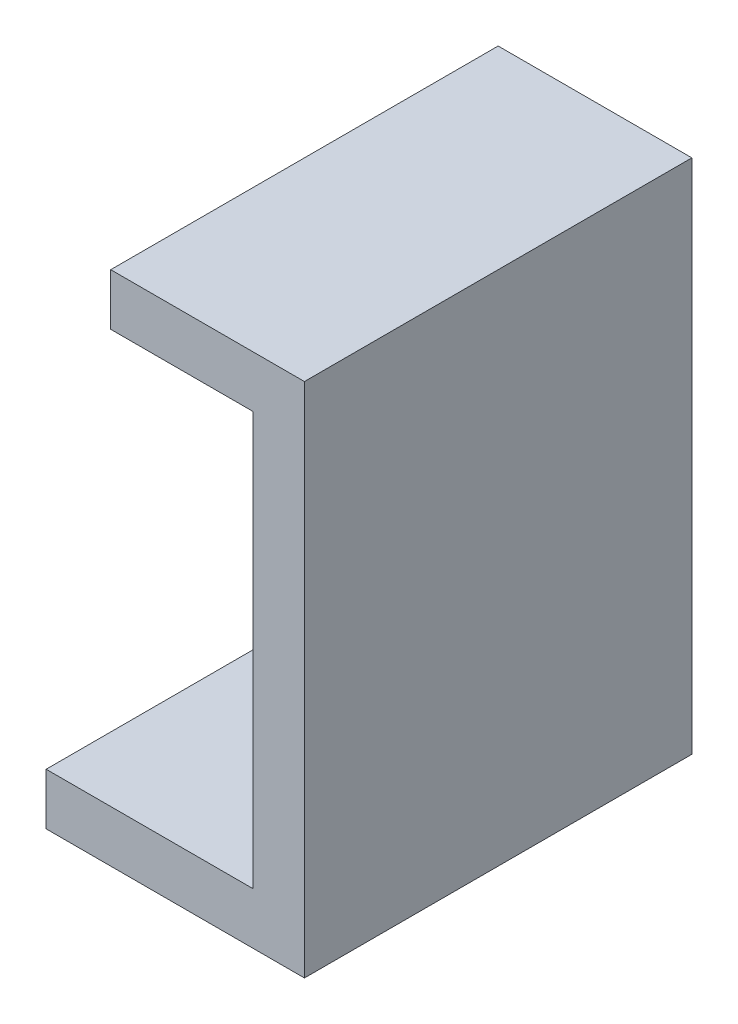
SolidWorks part; units mm, degrees
ref_plane "Front Plane" through (0, 0, 0) normal (0, 0, 1) x (1, 0, 0)
ref_plane "Top Plane" through (0, 0, 0) normal (0, 1, 0) x (1, 0, 0)
ref_plane "Right Plane" through (0, 0, 0) normal (1, 0, 0) x (0, 0, -1)
sketch "Sketch1" plane through (0, 0, 0) normal (0, 0, 1) x (1, 0, 0)
  line L0 (-21.234, 34.8873) -> (-21.234, 29.8073)
  line L1 (-21.234, 29.8073) -> (-7.264, 29.8073)
  line L2 (-7.264, 29.8073) -> (-7.264, -10.8327)
  line L3 (-7.264, -10.8327) -> (-27.584, -10.8327)
  line L4 (-27.584, -10.8327) -> (-27.584, -15.9127)
  line L5 (-27.584, -15.9127) -> (-2.184, -15.9127)
  line L6 (-2.184, -15.9127) -> (-2.184, 34.8873)
  line L7 (-2.184, 34.8873) -> (-21.234, 34.8873)
  dimension "D1" = 19.05
  dimension "D2" = 25.4
  dimension "D3" = 5.08
  dimension "D4" = 5.08
  dimension "D5" = 5.08
  dimension "D6" = 50.8
extrude "Boss-Extrude1" add sketch "Sketch1" along normal blind 38.1
